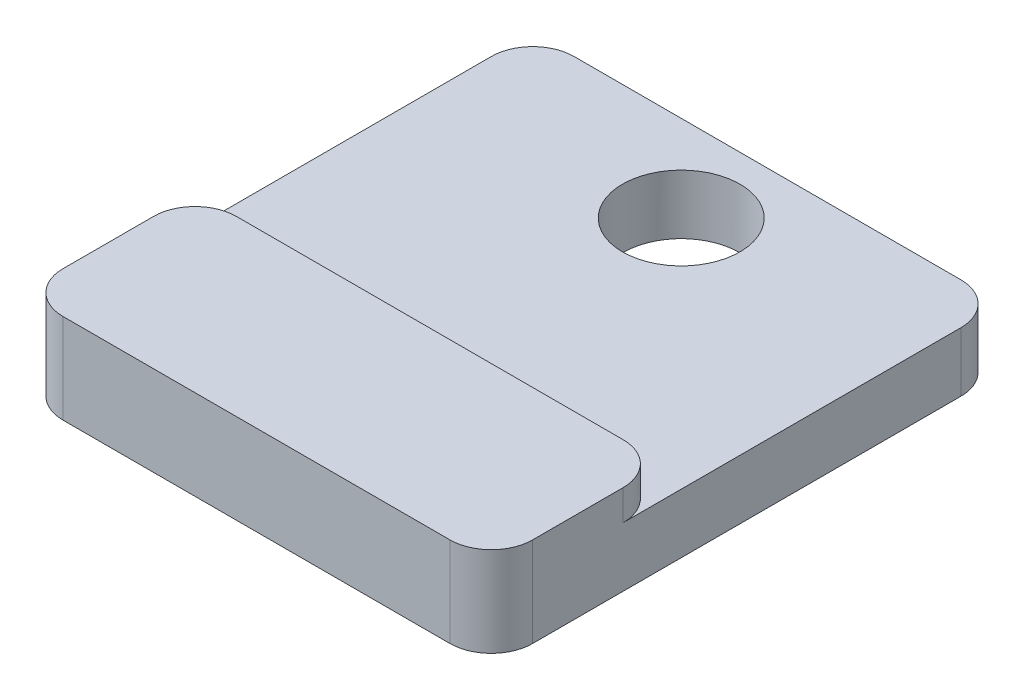
SolidWorks part; units mm, degrees
material "ABS"
ref_plane "Front Plane" through (0, 0, 0) normal (0, 0, 1) x (1, 0, 0)
ref_plane "Top Plane" through (0, 0, 0) normal (0, 1, 0) x (1, 0, 0)
ref_plane "Right Plane" through (0, 0, 0) normal (1, 0, 0) x (0, 0, -1)
sketch "Sketch1" plane through (0, 0, 0) normal (0, 1, 0) x (1, 0, 0)
  line L1 (0, 0) -> (215.9, 0)
  line L2 (0, 0) -> (0, 234.95)
  line L3 (0, 234.95) -> (215.9, 234.95)
  line L4 (215.9, 0) -> (215.9, 234.95)
  dimension "D1" = 234.95
  dimension "D2" = 215.9
extrude "Boss-Extrude1" add sketch "Sketch1" along normal blind 41.275
fillet "Fillet1" radius 19.05 4 edges at (0, 20.6375, -234.95) (215.9, 20.6375, -234.95) (215.9, 20.6375, 0) (0, 20.6375, 0)
sketch "Sketch3" plane through (0, 41.275, 0) normal (0, 1, 0) x (1, 0, 0)
  line L0 (107.95, 234.95) -> (107.95, 0) construction
  line L1 (196.85, 234.95) -> (19.05, 234.95) construction
  line L2 (19.05, 0) -> (196.85, 0) construction
  circle A0 centre (107.95, 195.2625) radius 26.9875
  point P8 (107.95, 222.25)
  dimension "D1" = 53.975
  dimension "D2" = 12.7
extrude "Cut-Extrude1" cut sketch "Sketch3" against normal up to next
sketch "Sketch4" plane through (0, 41.275, 0) normal (0, 1, 0) x (1, 0, 0)
  line L0 (215.9, 79.6925) -> (0, 79.6925)
  line L1 (215.9, 19.05) -> (215.9, 215.9) construction
  line L3 (196.85, 234.95) -> (19.05, 234.95) construction
  line L4 (0, 215.9) -> (0, 19.05) construction
  line L6 (196.85, 234.95) -> (19.05, 234.95)
  line L7 (215.9, 79.6925) -> (215.9, 215.9)
  line L8 (0, 215.9) -> (0, 79.6925)
  line L9 (19.05, 0) -> (196.85, 0) construction
  arc A0 (19.05, 234.95) -> (0, 215.9) centre (19.05, 215.9) ccw construction
  arc A1 (215.9, 215.9) -> (196.85, 234.95) centre (196.85, 215.9) ccw construction
  arc A4 (19.05, 234.95) -> (0, 215.9) centre (19.05, 215.9) ccw
  arc A5 (215.9, 215.9) -> (196.85, 234.95) centre (196.85, 215.9) ccw
  dimension "D1" = 79.6925
extrude "Cut-Extrude2" cut sketch "Sketch4" against normal blind 13.97
fillet "Fillet2" radius 19.05 2 edges at (0, 34.29, -79.6925) (215.9, 34.29, -79.6925)
